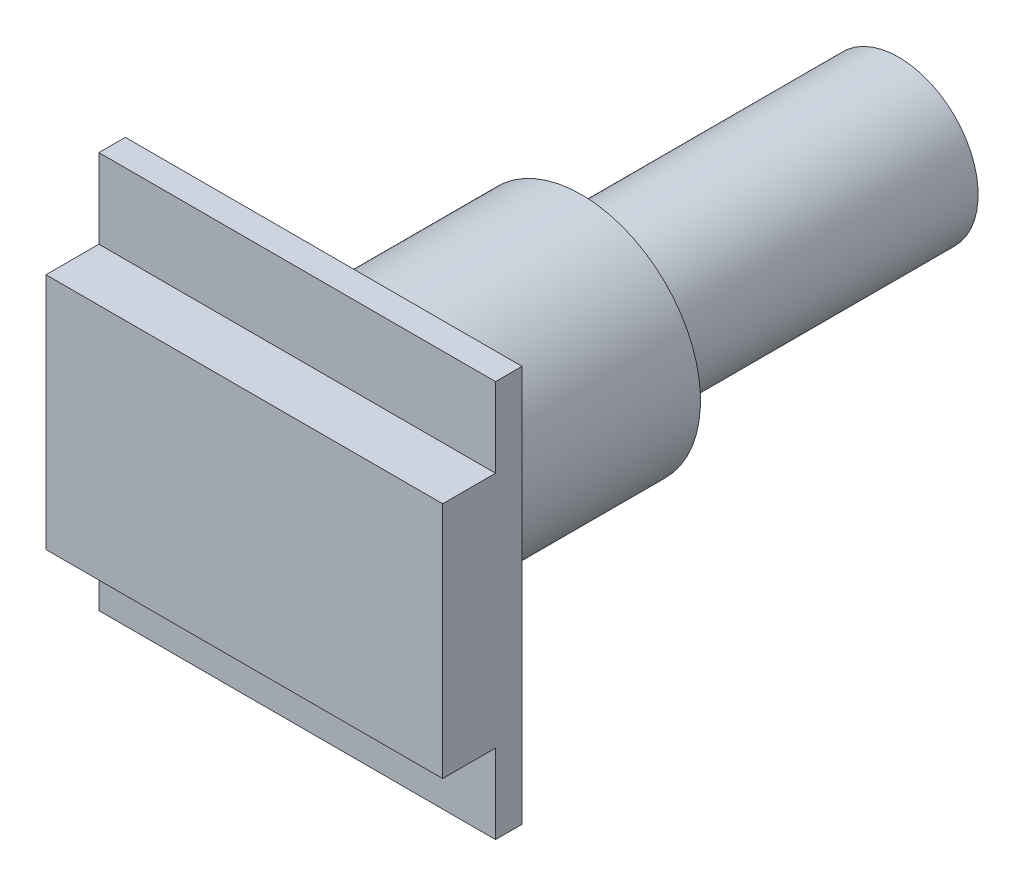
SolidWorks part; units mm, degrees
ref_plane "Ön Düzlem" through (0, 0, 0) normal (0, 0, 1) x (1, 0, 0)
ref_plane "Üst Düzlem" through (0, 0, 0) normal (0, 1, 0) x (1, 0, 0)
ref_plane "Sağ Düzlem" through (0, 0, 0) normal (1, 0, 0) x (0, 0, -1)
sketch "Çizim1" plane through (0, 0, 0) normal (0, 0, 1) x (1, 0, 0)
  line L1 (-39.1932, 23.6905) -> (-9.1932, 23.6905)
  line L2 (-39.1932, 23.6905) -> (-39.1932, -6.3095)
  line L3 (-39.1932, -6.3095) -> (-9.1932, -6.3095)
  line L4 (-9.1932, 23.6905) -> (-9.1932, -6.3095)
  dimension "D1" = 30
  dimension "D2" = 30
extrude "Yükseklik-Ekstrüzyon1" add sketch "Çizim1" along normal blind 6
sketch "Çizim2" plane through (0, 0, 6) normal (0, 0, 1) x (1, 0, 0)
  line L0 (-39.1932, -6.3095) -> (-39.1932, -0.3095)
  line L1 (-39.1932, 23.6905) -> (-39.1932, -6.3095) construction
  line L2 (-39.1932, -0.3095) -> (-9.1932, -0.3095)
  line L3 (-9.1932, -6.3095) -> (-9.1932, 23.6905) construction
  line L4 (-9.1932, -0.3095) -> (-9.1932, -6.3095)
  line L5 (-9.1932, -6.3095) -> (-39.1932, -6.3095)
  dimension "D1" = 6
extrude "Kes-Ekstrüzyon1" cut sketch "Çizim2" against normal blind 4
sketch "Çizim3" plane through (0, 0, 6) normal (0, 0, 1) x (1, 0, 0)
  line L0 (-39.1932, 23.6905) -> (-39.1932, 17.6905)
  line L1 (-39.1932, 23.6905) -> (-39.1932, -0.3095) construction
  line L2 (-39.1932, 23.6905) -> (-9.1932, 23.6905)
  line L3 (-9.1932, 23.6905) -> (-9.1932, 17.6905)
  line L4 (-9.1932, -0.3095) -> (-9.1932, 23.6905) construction
  line L5 (-9.1932, 17.6905) -> (-39.1932, 17.6905)
  dimension "D1" = 6
extrude "Kes-Ekstrüzyon2" cut sketch "Çizim3" against normal blind 4
sketch "Çizim4" plane through (0, 0, 0) normal (0, 0, -1) x (-1, 0, 0)
  line L0 (9.1932, -6.3095) -> (9.1932, 23.6905) construction
  line L1 (9.1932, 23.6905) -> (39.1932, 23.6905) construction
  circle A0 centre (24.1932, 8.6905) radius 9
  point P6 (0, 0)
  dimension "D1" = 15
  dimension "D2" = 15
extrude "Yükseklik-Ekstrüzyon2" add sketch "Çizim4" along normal blind 19.5
sketch "Çizim5" plane through (0, 0, -19.5) normal (0, 0, -1) x (-1, 0, 0)
  circle A0 centre (24.1932, 8.6905) radius 6
  circle A1 centre (24.1932, 8.6905) radius 9 construction
  dimension "D1" = 0
extrude "Yükseklik-Ekstrüzyon3" add sketch "Çizim5" along normal blind 24
